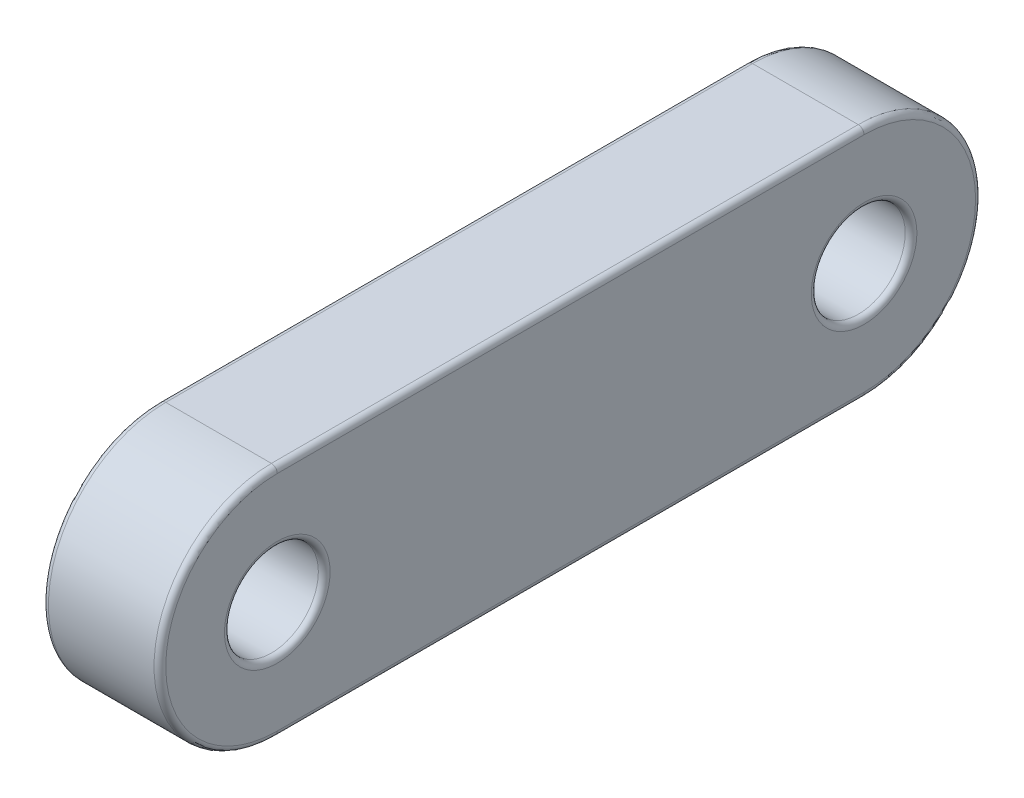
SolidWorks part; units mm, degrees
ref_plane "前视基准面" through (0, 0, 0) normal (0, 0, 1) x (1, 0, 0)
ref_plane "上视基准面" through (0, 0, 0) normal (0, 1, 0) x (1, 0, 0)
ref_plane "右视基准面" through (0, 0, 0) normal (1, 0, 0) x (0, 0, -1)
other "Configuration Table"
sketch "草图1" plane through (0, 0, 0) normal (1, 0, 0) x (0, 0, -1)
  line L0 (0, 0) -> (50, 0) construction
  line L1 (0, 10) -> (50, 10)
  line L2 (0, -10) -> (50, -10)
  arc A0 (0, 10) -> (0, -10) centre (0, 0) ccw
  arc A1 (50, -10) -> (50, 10) centre (50, 0) ccw
  circle A2 centre (0, 0) radius 4
  circle A3 centre (50, 0) radius 4
  point P3 (25, 0)
  dimension "D2" = 10
  dimension "D3" = 8
  dimension "D4" = 8
  dimension "D1" = 50
extrude "凸台-拉伸1" add sketch "草图1" along normal mid plane 10
fillet "圆角1" radius 0.5 12 edges at (-5, 0, -54) (-5, 0, -4) (-5, -10, -25) (-5, 0, -60) (-5, 10, -25) (-5, 0, 10) (5, 0, -54) (5, 10, -25) (5, 0, -60) (5, -10, -25) (5, 0, 10) (5, 0, -4)
